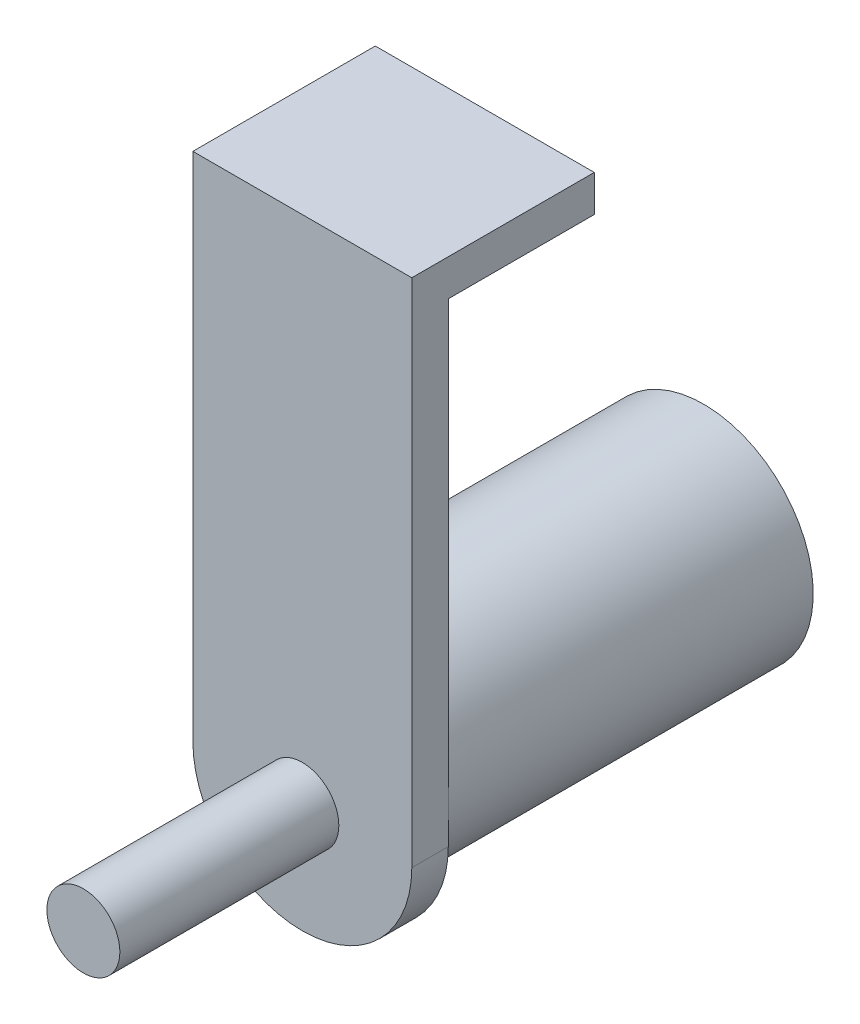
SolidWorks part; units mm, degrees
ref_plane "Plan de face" through (0, 0, 0) normal (0, 0, 1) x (1, 0, 0)
ref_plane "Plan de dessus" through (0, 0, 0) normal (0, 1, 0) x (1, 0, 0)
ref_plane "Plan de droite" through (0, 0, 0) normal (1, 0, 0) x (0, 0, -1)
sketch "Esquisse1" plane through (0, 0, 0) normal (0, 0, 1) x (1, 0, 0)
  line L0 (-15, 35) -> (15, 35)
  line L1 (15, 35) -> (15, -35)
  line L2 (-15, 35) -> (-15, -35)
  arc A0 (-15, -35) -> (15, -35) centre (0, -35) ccw
  circle A1 centre (0, -35) radius 0.7602
  dimension "D4" = 15
  dimension "D5" = 70
  dimension "D1" = 35
  dimension "D2" = 30
  dimension "D3" = 15
extrude "Boss.-Extru.1" add sketch "Esquisse1" along normal blind 5
sketch "Esquisse2" plane through (0, 0, 0) normal (0, 0, -1) x (-1, 0, 0)
  line L0 (15, 35) -> (15, -35) construction
  line L1 (-15, 35) -> (15, 35)
  line L2 (-15, 35) -> (-15, 30)
  line L3 (-15, 30) -> (15, 30)
  line L4 (15, 35) -> (15, 30)
  dimension "D1" = 5
extrude "Boss.-Extru.2" add sketch "Esquisse2" along normal blind 20
sketch "Esquisse4" plane through (0, 0, 5) normal (0, 0, 1) x (1, 0, 0)
  circle A0 centre (0, -35) radius 5
  dimension "D1" = 10
extrude "Boss.-Extru.3" add sketch "Esquisse4" along normal blind 15
sketch "Esquisse5" plane through (0, 0, 0) normal (0, 0, -1) x (-1, 0, 0)
  line L0 (-15, -35) -> (-15, 30) construction
  line L1 (15, 30) -> (15, -35) construction
  circle A0 centre (0, -30) radius 15
  point P9 (0, 0)
  dimension "D1" = 30
extrude "Boss.-Extru.4" add sketch "Esquisse5" along normal blind 50
sketch "Esquisse7" plane through (0, 0, 20) normal (0, 0, 1) x (1, 0, 0)
  circle A0 centre (0, -35) radius 5
  circle A1 centre (0, -35) radius 5
  point P4 (0, -35)
  circle M1 centre (0, -35) radius 5
sketch "Esquisse8" plane through (0, 0, 20) normal (0, 0, 1) x (1, 0, 0)
  line L1 (-0.05, -35.05) -> (0.05, -35.05)
  line L2 (-0.05, -35.05) -> (-0.05, -34.95)
  line L3 (-0.05, -34.95) -> (0.05, -34.95)
  line L4 (0.05, -35.05) -> (0.05, -34.95)
  dimension "D1" = 0.05
  dimension "D2" = 0.1
  dimension "D3" = 0.05
  dimension "D4" = 0.05
extrude "Enlèv. mat.-Extru.1" cut sketch "Esquisse8" against normal blind 15
extrude "Boss.-Extru.6" add sketch "Esquisse7" along normal blind 15 contours M1
